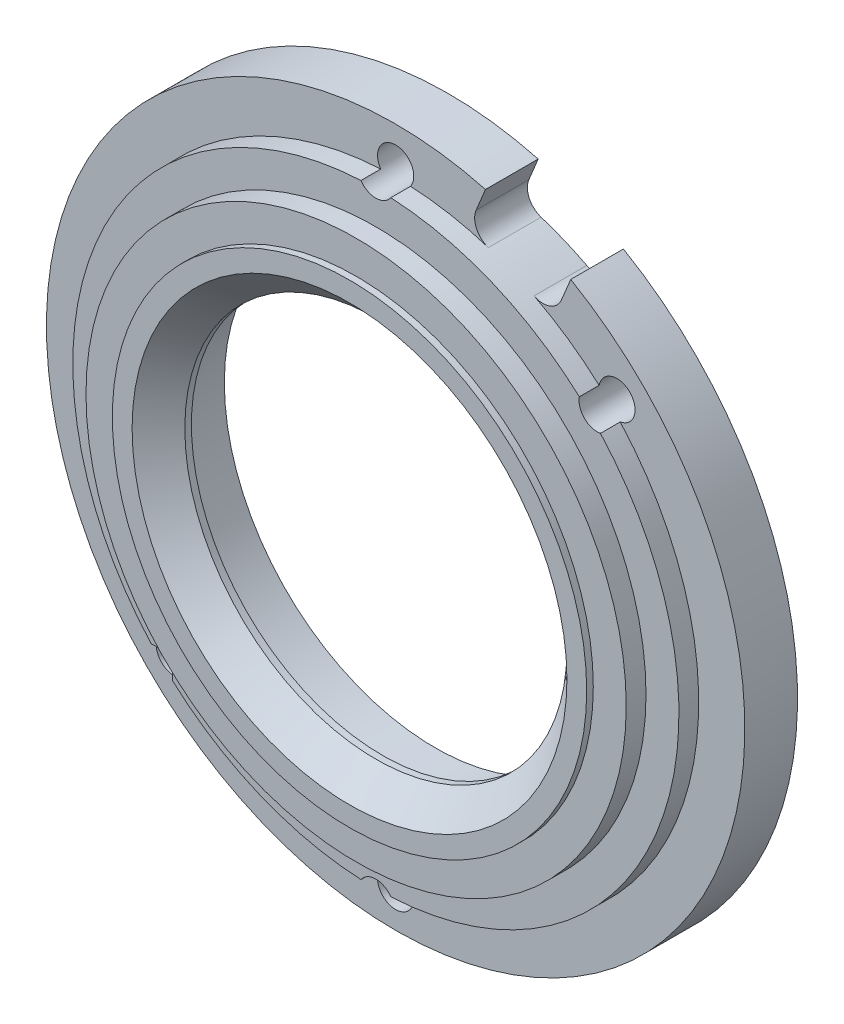
SolidWorks part; units mm, degrees
material "Oak"
ref_plane "Front Plane" through (0, 0, 0) normal (0, 0, 1) x (1, 0, 0)
ref_plane "Top Plane" through (0, 0, 0) normal (0, 1, 0) x (1, 0, 0)
ref_plane "Right Plane" through (0, 0, 0) normal (1, 0, 0) x (0, 0, -1)
sketch "Sketch1" plane through (0, 0, 0) normal (1, 0, 0) x (0, 0, -1)
  line L0 (0, 0) -> (83.5909, 0) construction
  line L1 (5, 29) -> (5, 32)
  line L14 (0, 29) -> (0, 36)
  line L15 (0, 36) -> (1, 36)
  line L16 (1, 36) -> (1, 41)
  line L17 (1, 41) -> (4, 41)
  line L18 (4, 41) -> (4, 46)
  line L19 (4, 46) -> (7, 46)
  line L20 (7, 46) -> (7, 53)
  line L26 (15, 53) -> (15, 32)
  line L27 (5, 29) -> (0, 29)
  line L28 (5, 32) -> (15, 32)
  line L29 (7, 53) -> (15, 53)
  dimension "D1" = 1
  dimension "D2" = 7
  dimension "D3" = 92
  dimension "D4" = 3
  dimension "D5" = 3
  dimension "D6" = 5
  dimension "D7" = 15
  dimension "D8" = 5
  dimension "D9" = 58
  dimension "D13" = 5
  dimension "D14" = 64
revolve "Revolve1" add sketch "Sketch1" angle 360 about L0
chamfer "Chamfer1" distance 4 angle 45 1 edges at (29, 0, 0)
sketch "Sketch5" plane through (0, 0, -15) normal (0, 0, -1) x (-1, 0, 0)
  circle A0 centre (0, 47.5) radius 2.75
  circle A4 centre (33.5876, 33.5876) radius 2.75 [skipped]
  circle A5 centre (47.5, 0) radius 2.75 [skipped]
  circle A6 centre (33.5876, -33.5876) radius 2.75
  circle A7 centre (0, -47.5) radius 2.75
  circle A8 centre (-33.5876, -33.5876) radius 2.75 [skipped]
  circle A9 centre (-47.5, 0) radius 2.75 [skipped]
  circle A10 centre (-33.5876, 33.5876) radius 2.75
  point P20 (0, 0)
  dimension "D1" = 5.5
  dimension "D2" = 47.5
  dimension "D3" = 8
extrude "Cut-Extrude4" cut sketch "Sketch5" against normal blind 20
sketch "Sketch6" plane through (0, 0, -7) normal (0, 0, 1) x (1, 0, 0)
  line L0 (0, 47.5) -> (33.5876, 33.5876) construction
  line L1 (0, 0) -> (16.7938, 40.5438) construction
  line L2 (26.5717, 45.8579) -> (23.8656, 39.3247)
  line L3 (13.6374, 51.2154) -> (10.9313, 44.6823)
  circle A0 centre (0, 0) radius 53 construction
  arc A1 (26.5717, 45.8579) -> (13.6374, 51.2154) centre (0, 0) ccw
  circle A2 centre (0, 0) radius 46 construction
  arc A3 (23.8656, 39.3247) -> (10.9313, 44.6823) centre (0, 0) ccw
  dimension "D1" = 14
extrude "Cut-Extrude5" cut sketch "Sketch6" against normal through all
fillet "Fillet2" radius 3 2 edges at (23.8656, 39.3247, -11) (10.9313, 44.6823, -11)
sketch "Sketch7" plane through (0, 0, -15) normal (0, 0, -1) x (-1, 0, 0)
  circle A0 centre (0, 0) radius 42.25
  dimension "D1" = 84.5
extrude "Cut-Extrude6" cut sketch "Sketch7" against normal blind 2
sketch "Sketch8" plane through (0, 0, -13) normal (0, 0, -1) x (-1, 0, 0)
  circle A0 centre (0, 0) radius 42.25
  circle A1 centre (0, 0) radius 40.25
  dimension "D1" = 84.5
  dimension "D2" = 80.5
extrude "Cut-Extrude7" cut sketch "Sketch8" against normal blind 4
